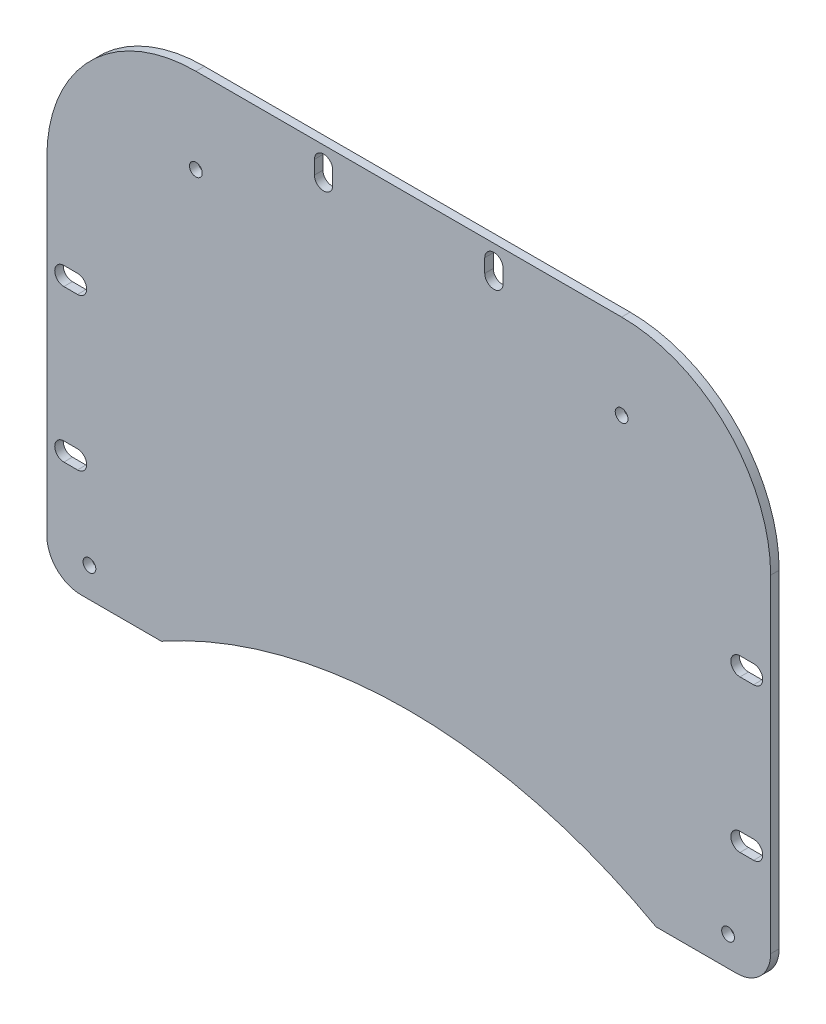
SolidWorks part; units mm, degrees
ref_plane "Front Plane" through (0, 0, 0) normal (0, 0, 1) x (1, 0, 0)
ref_plane "Top Plane" through (0, 0, 0) normal (0, 1, 0) x (1, 0, 0)
ref_plane "Right Plane" through (0, 0, 0) normal (1, 0, 0) x (0, 0, -1)
sketch "Sketch1" plane through (0, 0, 0) normal (0, 0, 1) x (1, 0, 0)
  line L0 (0, 175.4578) -> (0, -175.4578) construction
  line L1 (105.4801, 0) -> (-105.4801, 0) construction
  line L2 (-59.8749, -38) -> (-105.4801, -38) construction
  line L3 (85, 40) -> (85, -45)
  line L4 (50, 75) -> (-50, 75)
  line L5 (-58.0948, -45) -> (-105.4801, -45) construction
  line L6 (85, 73.1632) -> (85, -73.1632) construction
  line L7 (85, -45) -> (58.0948, -45)
  line L8 (-58.0948, -45) -> (-85, -45)
  line L9 (0, 73.1632) -> (0, -73.1632) construction
  line L10 (105.4801, -45) -> (-105.4801, -45) construction
  line L11 (105.4801, -45) -> (58.0948, -45) construction
  line L12 (-107.3168, 75) -> (117.2174, 75) construction
  line L13 (-107.3168, 55) -> (117.2174, 55) construction
  line L14 (-73.5, -38) -> (-76.5, -38)
  line L15 (105.4801, -38) -> (59.8749, -38) construction
  line L16 (-85, 127.5677) -> (-85, -91.289) construction
  line L17 (-81, 127.5677) -> (-81, -91.289) construction
  line L18 (105.4801, 20) -> (-105.4801, 20) construction
  line L19 (105.4801, -20) -> (-105.4801, -20) construction
  line L20 (105.4801, 17.85) -> (-105.4801, 17.85) construction
  line L21 (-81, 17.85) -> (-77.8, 17.85) construction
  line L22 (-81, 19.9983) -> (-77.8, 19.9983)
  line L23 (-81, 15.7017) -> (-77.8, 15.7017)
  line L24 (-81, -17.85) -> (-77.8, -17.85) construction
  line L25 (-81, -19.9983) -> (-77.8, -19.9983)
  line L26 (-81, -15.7017) -> (-77.8, -15.7017)
  line L27 (81, -17.85) -> (77.8, -17.85) construction
  line L28 (-85, 40) -> (-85, -45)
  line L29 (-50, 175.4578) -> (-50, -175.4578) construction
  line L30 (50, 175.4578) -> (50, -175.4578) construction
  line L31 (105.4801, 75) -> (-105.4801, 75) construction
  line L32 (-107.3168, 71) -> (117.2174, 71) construction
  line L33 (81, -19.9983) -> (77.8, -19.9983)
  line L34 (81, -15.7017) -> (77.8, -15.7017)
  line L35 (81, 17.85) -> (77.8, 17.85) construction
  line L36 (81, 19.9983) -> (77.8, 19.9983)
  line L37 (81, 15.7017) -> (77.8, 15.7017)
  line L38 (-20, 175.4578) -> (-20, -175.4578) construction
  line L39 (20, 175.4578) -> (20, -175.4578) construction
  line L40 (-20, 71) -> (-20, 67.8) construction
  line L41 (-17.85, 71) -> (-17.85, 67.8)
  line L42 (-22.15, 71) -> (-22.15, 67.8)
  line L43 (20, 71) -> (20, 67.8) construction
  line L44 (17.85, 71) -> (17.85, 67.8)
  line L45 (22.15, 71) -> (22.15, 67.8)
  arc A0 (58.0948, -45) -> (-58.0948, -45) centre (0, -150) ccw
  circle A1 centre (-75, -38) radius 1.5
  arc A2 (59.8749, -38) -> (-59.8749, -38) centre (0, -150) ccw construction
  arc A3 (-81, 19.9983) -> (-81, 15.7017) centre (-81, 17.85) ccw
  arc A4 (-77.8, 15.7017) -> (-77.8, 19.9983) centre (-77.8, 17.85) ccw
  arc A5 (-81, -19.9983) -> (-81, -15.7017) centre (-81, -17.85) cw
  arc A6 (-77.8, -15.7017) -> (-77.8, -19.9983) centre (-77.8, -17.85) cw
  arc A7 (81, -19.9983) -> (81, -15.7017) centre (81, -17.85) ccw
  arc A8 (77.8, -15.7017) -> (77.8, -19.9983) centre (77.8, -17.85) ccw
  arc A9 (81, 19.9983) -> (81, 15.7017) centre (81, 17.85) cw
  arc A10 (77.8, 15.7017) -> (77.8, 19.9983) centre (77.8, 17.85) cw
  circle A11 centre (75, -38) radius 1.5
  circle A12 centre (50, 55) radius 1.5
  arc A13 (-85, 40) -> (-50, 75) centre (-50, 40) cw
  arc A14 (85, 40) -> (50, 75) centre (50, 40) ccw
  circle A15 centre (-50, 55) radius 1.5
  arc A16 (-17.85, 71) -> (-22.15, 71) centre (-20, 71) ccw
  arc A17 (-22.15, 67.8) -> (-17.85, 67.8) centre (-20, 67.8) ccw
  arc A18 (17.85, 71) -> (22.15, 71) centre (20, 71) cw
  arc A19 (22.15, 67.8) -> (17.85, 67.8) centre (20, 67.8) cw
  point P47 (-79.4, 17.85)
  point P54 (-79.4, -17.85)
  point P61 (79.4, -17.85)
  point P78 (79.4, 17.85)
  point P93 (-20, 69.4)
  point P100 (20, 69.4)
  dimension "D6" = 20
  dimension "D5" = 120
  dimension "D9" = 3
  dimension "D10" = 50
  dimension "D12" = 20
  dimension "D11" = 4
  dimension "D15" = 20
  dimension "D13" = 35
  dimension "D18" = 116.1895
  dimension "D20" = 2.1483
  dimension "D22" = 3
  dimension "D23" = 20
  dimension "D25" = 2.15
  dimension "D16" = 85
  dimension "D17" = 10
  dimension "D21" = 3.2
  dimension "D26" = 3.2
  dimension "D2" = 85
  dimension "D3" = 75
  dimension "D4" = 45
  dimension "D7" = 50
  dimension "D8" = 7
  dimension "D14" = 4
  dimension "D19" = 2.15
  dimension "D24" = 20
extrude "Boss-Extrude1" add sketch "Sketch1" along normal blind 2 contours L3 A14 L4 A13 L28 L8 A0 L7 A17 L42 A16 L41 A12 L37 A10 L36 A9 L26 A6 L25 A5 A1 A4 L23 A3 L22 A8 L34 A7 L33 A11 A15 L45 A19 L44 A18
fillet "Fillet1" radius 8 2 edges at (85, -45, 1) (-85, -45, 1)
